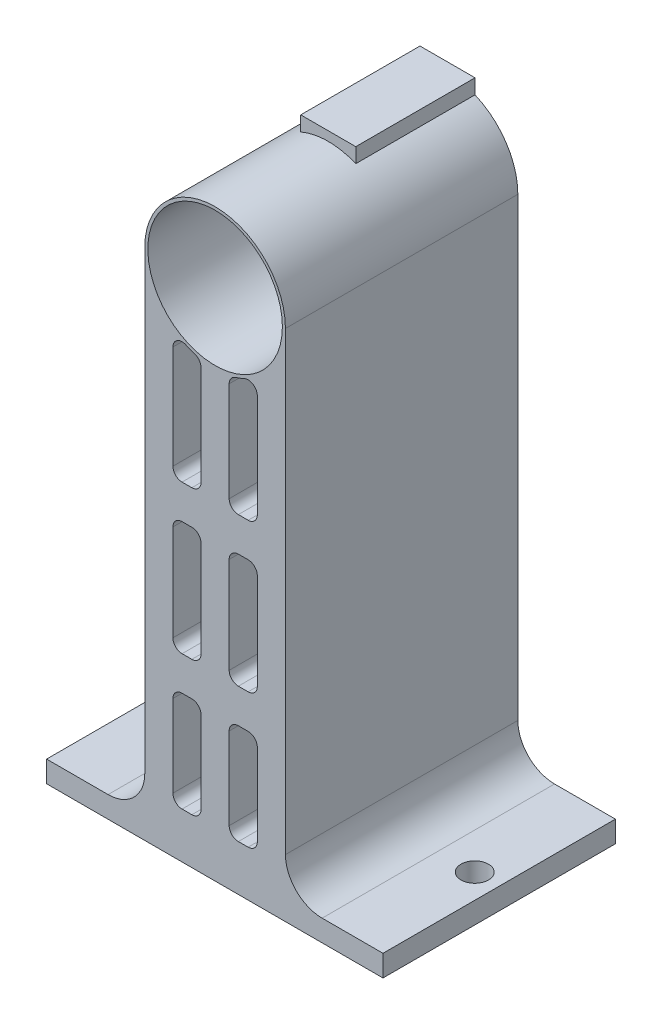
SolidWorks part; units mm, degrees
material "PLA"
ref_plane "Alzado" through (0, 0, 0) normal (0, 0, 1) x (1, 0, 0)
ref_plane "Planta" through (0, 0, 0) normal (0, 1, 0) x (1, 0, 0)
ref_plane "Vista lateral" through (0, 0, 0) normal (1, 0, 0) x (0, 0, -1)
sketch "Croquis1" plane through (0, 0, 0) normal (0, 0, 1) x (1, 0, 0)
  line L0 (0, 40.6253) -> (0, -32.3747) construction
  circle A0 centre (0, 51.6253) radius 11
  circle A1 centre (0, 51.6253) radius 11.5
  dimension "D2" = 22
  dimension "D3" = 23
  dimension "D1" = 84
extrude "Saliente-Extruir1" add sketch "Croquis1" along normal blind 19
sketch "Croquis2" plane through (0, 0, 0) normal (0, 0, -1) x (-1, 0, 0)
  line L0 (0, 51.6253) -> (0, 63.1253) construction
  line L1 (-4, 64.1253) -> (4, 64.1253)
  line L2 (-4, 64.1253) -> (-4, 61.8723)
  line L3 (4, 64.1253) -> (4, 61.8723)
  line L4 (-4.5, 64.6253) -> (4.5, 64.6253)
  line L5 (4.5, 64.6253) -> (4.5, 62.2083)
  line L6 (-4.5, 64.6253) -> (-4.5, 62.2083)
  arc A1 (-4, 61.8723) -> (4, 61.8723) centre (0, 51.6253) ccw
  arc A2 (-4.5, 62.2083) -> (4.5, 62.2083) centre (0, 51.6253) ccw
  point P9 (0, 64.1253)
  dimension "D1" = 0.5
  dimension "D2" = 8
  dimension "D3" = 0.5
  dimension "D4" = 0.5
  dimension "D5" = 0.5
sketch "Croquis3" plane through (0, 0, 0) normal (0, 0, -1) x (-1, 0, 0)
  line L1 (-4.5, 64.6253) -> (4.5, 64.6253)
  line L2 (-4.5, 64.6253) -> (-4.5, 62.2083)
  line L4 (4.5, 64.6253) -> (4.5, 62.2083)
  arc A0 (4.5, 62.2083) -> (-4.5, 62.2083) centre (0, 51.6253) ccw
extrude "Saliente-Extruir2" add sketch "Croquis3" against normal blind 0.5
extrude "Saliente-Extruir3" add sketch "Croquis2" along normal blind 19
sketch "Croquis4" plane through (0, 0, 19) normal (0, 0, 1) x (1, 0, 0)
  line L0 (-11.5, 51.6253) -> (-11.5, -22.8747)
  line L1 (17.45, -32.3747) -> (17.45, -24.1132) construction
  line L2 (11.5, -22.8747) -> (11.5, 51.6253)
  line L3 (-27.55, -32.3747) -> (-11.55, -32.3747)
  line L4 (-17.55, -32.3747) -> (-17.55, -24.8747) construction
  line L5 (11.45, -32.3747) -> (27.45, -32.3747)
  line L6 (-27.55, -32.3747) -> (-27.55, -28.8747)
  line L7 (-27.55, -28.8747) -> (-17.5, -28.8747)
  line L8 (-11.55, -32.3747) -> (11.45, -32.3747)
  line L9 (-6.9, -24.8747) -> (-6.9, -8.4747)
  line L10 (27.45, -32.3747) -> (27.45, -28.8747)
  line L11 (27.45, -28.8747) -> (17.5, -28.8747)
  line L12 (6.9, -24.8747) -> (6.9, -8.4747)
  line L13 (-2.3, -24.8747) -> (-2.3, -8.4747)
  line L14 (2.3, -24.8747) -> (2.3, -8.4747)
  line L15 (-6.9, -24.8747) -> (-2.3, -24.8747)
  line L16 (6.9, -24.8747) -> (2.3, -24.8747)
  line L17 (-6.9, -8.4747) -> (-2.3, -8.4747)
  line L18 (2.3, -8.4747) -> (6.9, -8.4747)
  line L19 (6.9, -2.8747) -> (2.3, -2.8747)
  line L20 (-2.3, -2.8747) -> (-6.9, -2.8747)
  line L21 (6.9, 15.8253) -> (2.3, 15.8253)
  line L22 (6.9, 21.4253) -> (2.3, 21.4253)
  line L23 (-2.3, 15.8253) -> (-6.9, 15.8253)
  line L24 (-2.3, 21.4253) -> (-6.9, 21.4253)
  line L25 (-11.5, 51.6253) -> (-11.0095, 52.1159)
  line L26 (11.5, 51.6253) -> (10.9881, 52.1372)
  line L27 (0, 40.1253) -> (12.9287, 40.1253) construction
  line L28 (-6.9, 21.4253) -> (-6.9, 43.0324)
  line L29 (-2.3, 21.4253) -> (-2.3, 40.8721)
  line L30 (-6.9, -2.8747) -> (-6.9, 15.8253)
  line L31 (-2.3, -2.8747) -> (-2.3, 15.8253)
  line L32 (2.3, 21.4253) -> (2.3, 40.8244)
  line L33 (6.9, 21.4253) -> (6.9, 42.8575)
  line L34 (2.3, -2.8747) -> (2.3, 15.8253)
  line L35 (6.9, -2.8747) -> (6.9, 15.8253)
  circle A0 centre (0, 51.6253) radius 11.5 construction
  arc A2 (17.5, -28.8747) -> (11.5, -22.8747) centre (17.5, -22.8747) cw
  arc A3 (-17.5, -28.8747) -> (-11.5, -22.8747) centre (-17.5, -22.8747) ccw
  circle A4 centre (0, 51.6253) radius 11.5 construction
  circle A5 centre (0, 51.6253) radius 11
  point P17 (-19.55, -32.3747)
  circle M18 centre (0, 51.6253) radius 11.5
  dimension "D6" = 6
  dimension "D1" = 55
  dimension "D2" = 10
  dimension "D3" = 10
  dimension "D4" = 3.5
  dimension "D5" = 3.5
  dimension "D7" = 7.5
  dimension "D8" = 4.6
  dimension "D9" = 4.6
  dimension "D10" = 4.6
  dimension "D11" = 7.5
  dimension "D12" = 7.5
  dimension "D13" = 65
  dimension "D14" = 5.6
  dimension "D15" = 5.6
  dimension "D16" = 18.7
  dimension "D17" = 18.7
extrude "Saliente-Extruir4" add sketch "Croquis4" against normal blind 38 contours A3 L7 L6 L3 L8 L5 L10 L11 A2 L2 L12 L16 L14 L13 L15 L9 L0 M18
sketch "Croquis5" plane through (0, -28.8747, 0) normal (0, 1, 0) x (1, 0, 0)
  line L0 (-27.55, 19) -> (-27.55, -19) construction
  line L1 (27.45, 19) -> (27.45, -19) construction
  line L2 (-27.55, -19) -> (-17.5, -19) construction
  line L3 (27.45, -19) -> (17.5, -19) construction
  circle A0 centre (-23.55, 0) radius 2.25
  circle A1 centre (23.45, 0) radius 2.25
  dimension "D1" = 4.5
  dimension "D2" = 4.5
  dimension "D3" = 4
  dimension "D4" = 4
  dimension "D5" = 19
  dimension "D6" = 19
extrude "Cortar-Extruir1" cut sketch "Croquis5" against normal blind 38
fillet "Redondeo1" radius 1.5 24 edges at (-6.9, -24.8747, 0) (-2.3, -24.8747, 0) (2.3, -24.8747, 0) (6.9, -24.8747, 0) (-2.3, -8.4747, 0) (6.9, -8.4747, 0) (2.3, -8.4747, 0) (-6.9, -8.4747, 0) (2.3, 15.8253, 0) (-6.9, 15.8253, 0) (2.3, 40.3577, 0) (-6.9, 42.4253, 0) (-2.3, 15.8253, 0) (6.9, 15.8253, 0) (-2.3, 40.3577, 0) (6.9, 42.4253, 0) (6.9, 21.4253, 0) (-2.3, 21.4253, 0) (2.3, 21.4253, 0) (-6.9, 21.4253, 0) (-6.9, -2.8747, 0) (2.3, -2.8747, 0) (-2.3, -2.8747, 0) (6.9, -2.8747, 0)
